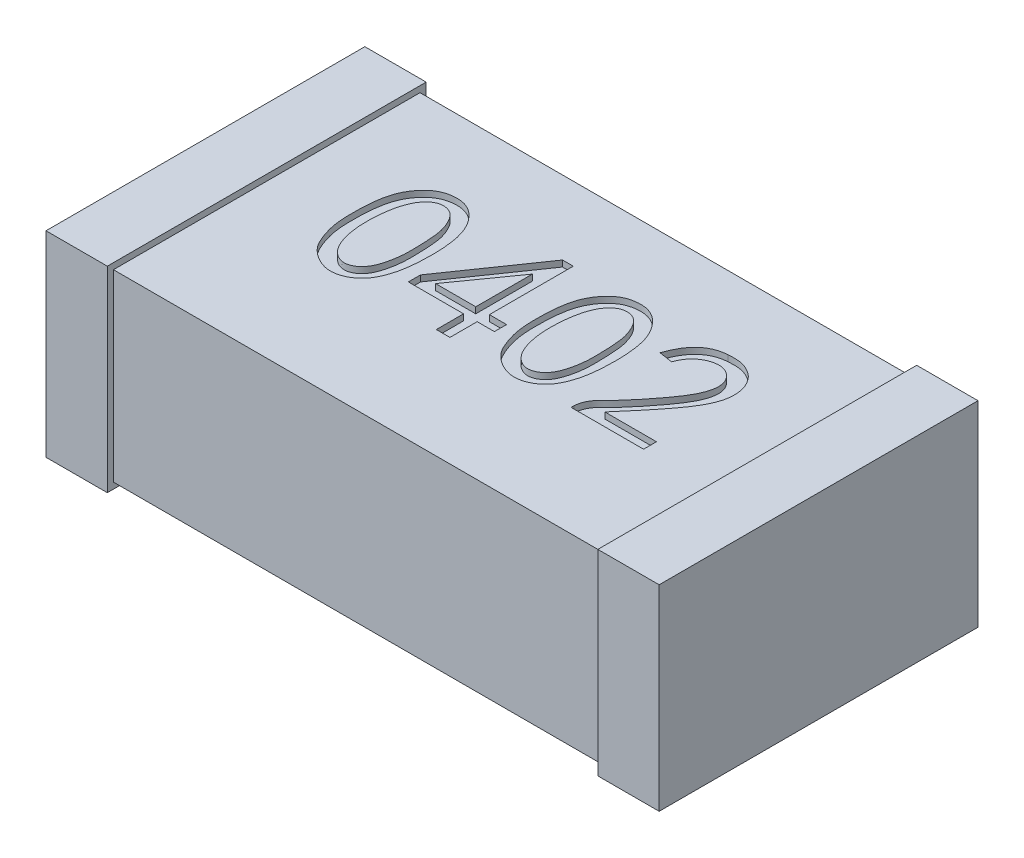
SolidWorks part; units mm, degrees
ref_plane "前视基准面" through (0, 0, 0) normal (0, 0, 1) x (1, 0, 0)
ref_plane "上视基准面" through (0, 0, 0) normal (0, 1, 0) x (1, 0, 0)
ref_plane "右视基准面" through (0, 0, 0) normal (1, 0, 0) x (0, 0, -1)
sketch "草图1" plane through (0, 0, 0) normal (0, 1, 0) x (1, 0, 0)
  line L0 (-31.3913, 0) -> (27.0565, 0) construction
  line L1 (0, 12.4242) -> (0, -8.2436) construction
  line L3 (-0.5, -0.25) -> (0.5, -0.25)
  line L4 (-0.5, -0.25) -> (-0.5, 0.25)
  line L5 (-0.5, 0.25) -> (0.5, 0.25)
  line L6 (0.5, -0.25) -> (0.5, 0.25)
  dimension "D1" = 1
  dimension "D2" = 0.5
extrude "凸台-拉伸1" add sketch "草图1" along normal blind 0.3
sketch "草图2" plane through (-0.5, 0, 0) normal (-1, 0, 0) x (0, 0, 1)
  line L0 (-0.2947, 0.15) -> (0.2931, 0.15) construction
  line L1 (-0.26, 0.31) -> (0.26, 0.31)
  line L2 (-0.26, 0.31) -> (-0.26, -0.01)
  line L3 (-0.26, -0.01) -> (0.26, -0.01)
  line L4 (0.26, 0.31) -> (0.26, -0.01)
  line L5 (0, -0.0313) -> (0, 0.3371) construction
  line L6 (-0.25, 0.3) -> (0.25, 0.3) construction
  dimension "D1" = 0.32
  dimension "D2" = 0.52
  dimension "D3" = 0.01
extrude "凸台-拉伸2" add sketch "草图2" against normal blind 0.1
sketch "草图3" plane through (0.5, 0, 0) normal (1, 0, 0) x (0, 0, -1)
  line L0 (-0.26, 0.31) -> (0.26, 0.31) construction
  line L1 (-0.26, -0.01) -> (-0.26, 0.31) construction
  line L2 (0.26, -0.01) -> (-0.26, -0.01) construction
  line L3 (0.26, 0.31) -> (0.26, -0.01) construction
  line L4 (-0.26, 0.31) -> (0.26, 0.31)
  line L5 (-0.26, -0.01) -> (-0.26, 0.31)
  line L6 (0.26, -0.01) -> (-0.26, -0.01)
  line L7 (0.26, 0.31) -> (0.26, -0.01)
extrude "凸台-拉伸3" add sketch "草图3" against normal blind 0.1
sketch "草图4" plane through (0, 0.3, 0) normal (0, 1, 0) x (1, 0, 0)
  text T0 "0402" font "黑体" height 0.2
extrude "切除-拉伸1" cut sketch "草图4" against normal blind 0.01
